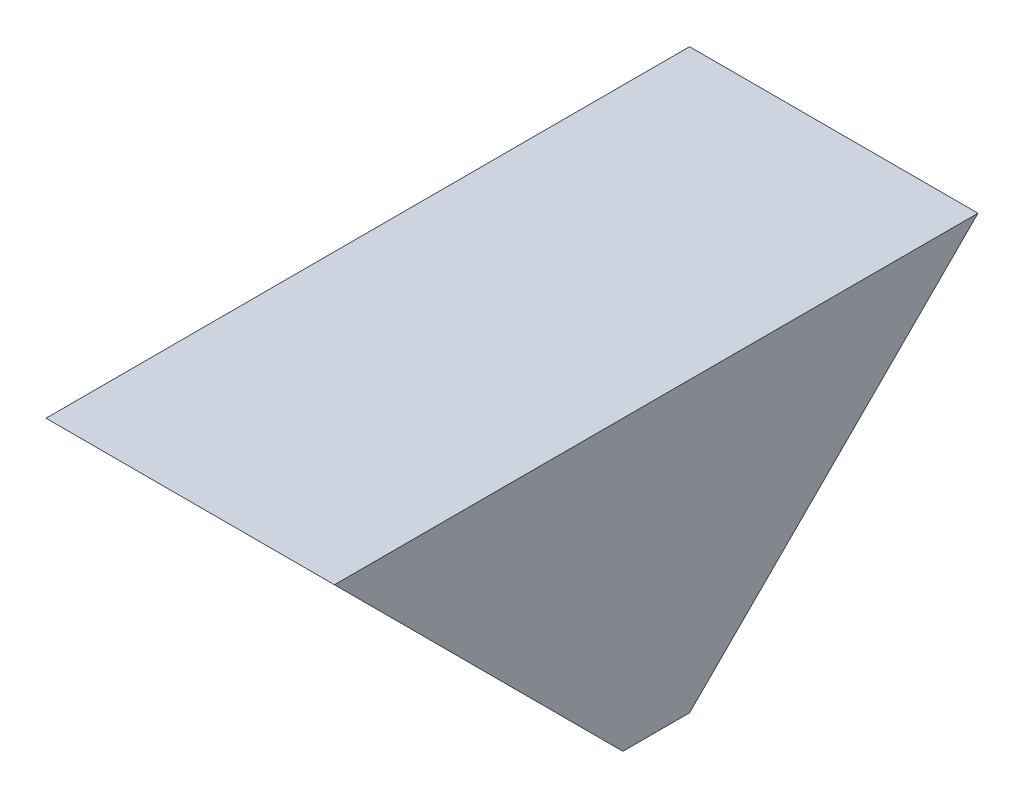
SolidWorks part; units mm, degrees
ref_plane "Alzado" through (0, 0, 0) normal (0, 0, 1) x (1, 0, 0)
ref_plane "Planta" through (0, 0, 0) normal (0, 1, 0) x (1, 0, 0)
ref_plane "Vista lateral" through (0, 0, 0) normal (1, 0, 0) x (0, 0, -1)
sketch "Croquis2" plane through (0, 0, 0) normal (0, 0, 1) x (1, 0, 0)
  line L0 (4.7625, -4.7625) -> (71.4375, -4.7625)
  line L1 (0, 0) -> (76.2, 0)
  line L2 (0, 0) -> (0, -76.2)
  line L3 (0, -76.2) -> (76.2, -76.2)
  line L4 (76.2, 0) -> (76.2, -76.2)
  line L5 (71.4375, -4.7625) -> (71.4375, -71.4375)
  line L6 (4.7625, -71.4375) -> (71.4375, -71.4375)
  line L7 (4.7625, -4.7625) -> (4.7625, -71.4375)
  dimension "D1" = 76.2
  dimension "D2" = 76.2
  dimension "D3" = 4.7625
extrude "Saliente-Extruir1" add sketch "Croquis2" against normal blind 170
sketch "Croquis3" plane through (76.2, 0, 0) normal (1, 0, 0) x (0, 0, -1)
  line L0 (0, 0) -> (76.2, -76.2)
  line L1 (170, -76.2) -> (0, -76.2) construction
  line L2 (0, -76.2) -> (0, 0) construction
  line L3 (170, 0) -> (93.8, -76.2)
  line L4 (170, -76.2) -> (170, 0) construction
  line L5 (0, 0) -> (0, -76.2)
  line L6 (0, -76.2) -> (76.2, -76.2)
  line L7 (170, 0) -> (170, -76.2)
  line L8 (170, -76.2) -> (93.8, -76.2)
  dimension "D1" = 45
  dimension "D2" = 45
extrude "Cortar-Extruir1" cut sketch "Croquis3" against normal up to surface (76.2 mm away) up to face at (0, -38.1, -85)
